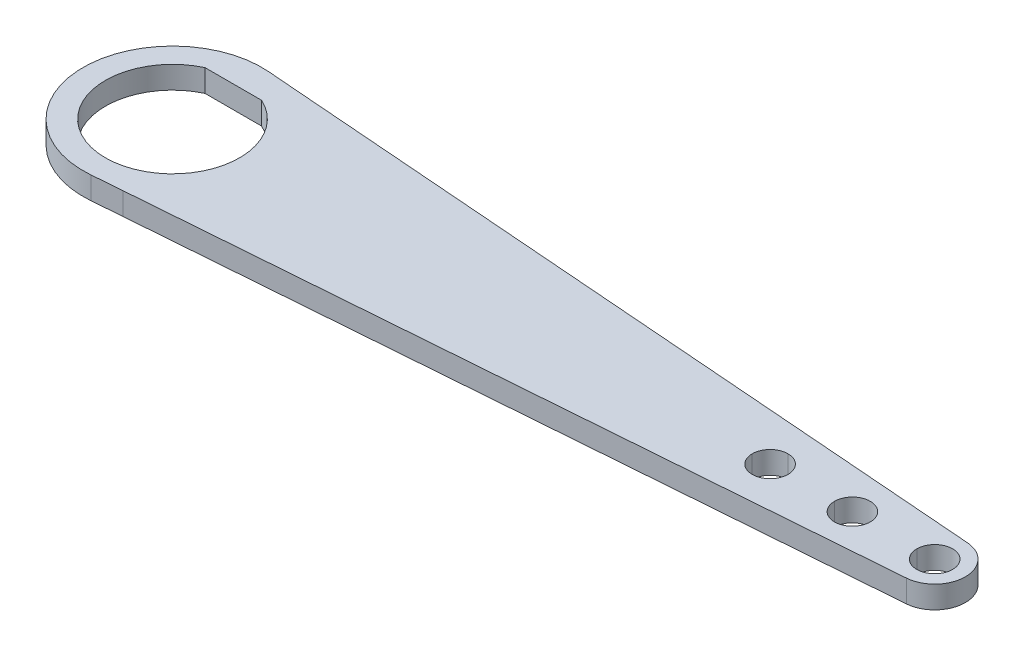
SolidWorks part; units mm, degrees
material "AISI 4130 Steel, annealed at 865C"
ref_plane "Front Plane" through (0, 0, 0) normal (0, 0, 1) x (1, 0, 0)
ref_plane "Top Plane" through (0, 0, 0) normal (0, 1, 0) x (1, 0, 0)
ref_plane "Right Plane" through (0, 0, 0) normal (1, 0, 0) x (0, 0, -1)
sketch "Sketch1" plane through (0, 0, 0) normal (0, 1, 0) x (1, 0, 0)
  line L3 (108.5391, 4.3352) -> (5.2635, 12.3186)
  line L4 (-55, 0) -> (55, 0) construction
  line L5 (108.5391, -4.3352) -> (5.2635, -12.3186)
  arc A2 (1.0518, -12.6564) -> (1.0518, 12.6564) centre (0, 0) cw
  arc A3 (108.5391, 4.3352) -> (108.5391, -4.3352) centre (108.204, 0) cw
  circle A4 centre (108.204, 0) radius 2.54
  circle A5 centre (96.52, 0) radius 2.54
  circle A6 centre (84.836, 0) radius 2.54
  arc A8 (5.2635, 12.3186) -> (1.0518, 12.6564) centre (61.7867, 743.5167) cw
  arc A9 (5.2635, -12.3186) -> (1.0518, -12.6564) centre (61.7867, -743.5167) ccw
  point P6 (9.0538, 10.1043)
  point P12 (6.6415, 11.5576)
  point P13 (5.2635, 12.3186)
  point P17 (0, 0)
  dimension "D1" = 5.08
  dimension "D3" = 12.7
  dimension "D4" = 5.08
  dimension "D5" = 11.684
  dimension "D2" = 96.52
  dimension "D6" = 11.684
sketch "Sketch3" plane through (0, 0, 0) normal (0, 1, 0) x (1, 0, 0)
  line L0 (-4.0181, 8.636) -> (4.0181, 8.636)
  arc A0 (4.0181, 8.636) -> (-4.0181, 8.636) centre (0, 0) cw
  point P3 (0, 8.636)
extrude "Boss-Extrude1" add sketch "Sketch1" along normal blind 3.175
extrude "Cut-Extrude1" cut sketch "Sketch3" against normal through all both and the other way through all
sketch "Sketch6" plane through (0, 0, 0) normal (0, -1, 0) x (1, 0, 0)
  line L0 (82.296, 0) -> (87.376, 0)
  line L1 (93.98, 0) -> (99.06, 0)
  line L2 (105.664, 0) -> (110.744, 0)
  line L3 (84.836, 2.54) -> (84.836, -2.54)
  circle A0 centre (84.836, 0) radius 2.54 construction
  circle A1 centre (96.52, 0) radius 2.54 construction
  circle A2 centre (108.204, 0) radius 2.54 construction
split line "Split Line1"
sketch "Sketch8" plane through (0, 0, 0) normal (0, -1, 0) x (1, 0, 0)
  line L0 (0, 0) -> (0, 4.0363)
